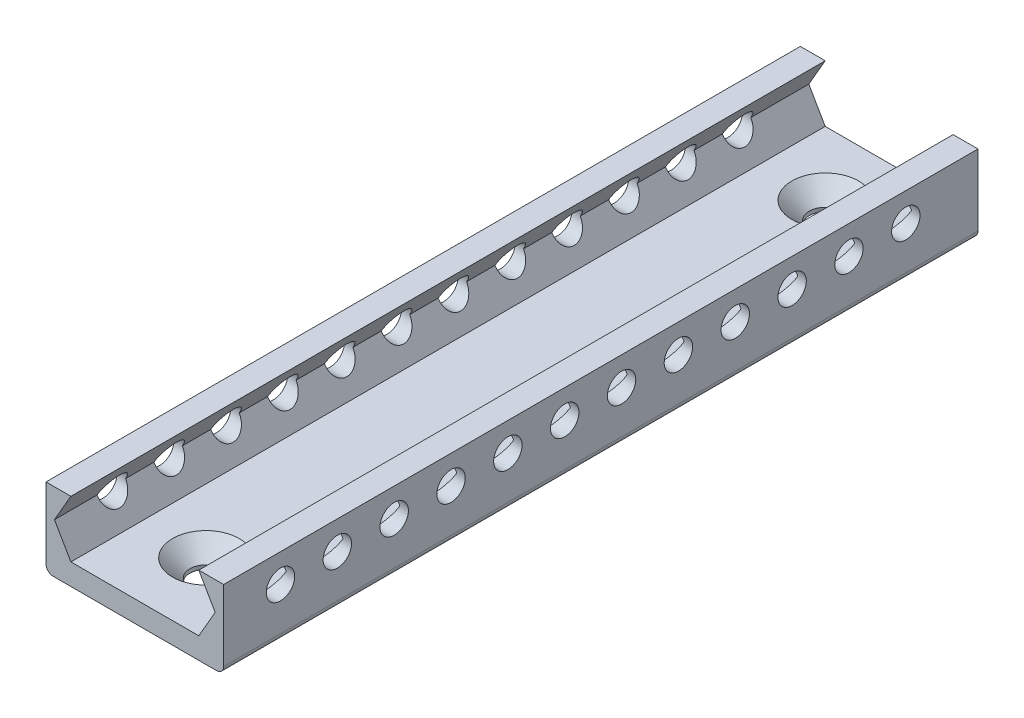
SolidWorks part; units mm, degrees
ref_plane "Front Plane" through (0, 0, 0) normal (0, 0, 1) x (1, 0, 0)
ref_plane "Top Plane" through (0, 0, 0) normal (0, 1, 0) x (1, 0, 0)
ref_plane "Right Plane" through (0, 0, 0) normal (1, 0, 0) x (0, 0, -1)
sketch "Sketch1" plane through (0, 0, 0) normal (0, 0, 1) x (1, 0, 0)
  line L0 (-9, 0) -> (9, 0)
  line L1 (-9, 0) -> (-11.3094, 4)
  line L2 (-11.3094, 4) -> (-9, 8)
  line L3 (-9, 8) -> (9, 8) construction
  line L4 (9, 8) -> (11.3094, 4)
  line L5 (11.3094, 4) -> (9, 0)
  line L6 (-9, 0) -> (-12.5, 0) construction
  line L8 (-12.5, 8) -> (-9, 8)
  line L9 (9, 8) -> (12.5, 8)
  line L10 (12.5, 8) -> (12.5, -3)
  line L11 (-12.5, 8) -> (-12.5, -3)
  line L12 (-12.5, -3) -> (12.5, -3)
  dimension "D1" = 18
  dimension "D2" = 120
  dimension "D3" = 120
  dimension "D4" = 120
  dimension "D5" = 120
  dimension "D6" = 8
  dimension "D7" = 3
  dimension "D8" = 3.5
extrude "Boss-Extrude1" add sketch "Sketch1" against normal blind 106.1617
sketch "Sketch2" plane through (0, 0, 0) normal (0, 1, 0) x (1, 0, 0)
  line L0 (9, 106.1617) -> (-9, 106.1617) construction
  line L1 (9, 0) -> (-9, 0) construction
  line L2 (0, 124.6082) -> (0, -49875.3918) construction
  circle A0 centre (0, 97.1617) radius 2
  circle A1 centre (0, 10) radius 2
  point P14 (0, 106.1617)
  dimension "D1" = 4
  dimension "D2" = 9
  dimension "D3" = 10
sketch "Sketch3" plane through (12.5, 0, 0) normal (1, 0, 0) x (0, 0, -1)
  line L0 (106.1617, 4) -> (0, 4) construction
  line L1 (0, -3) -> (0, 8) construction
  circle A0 centre (8, 4) radius 2
  dimension "D1" = 4
  dimension "D2" = 8
extrude "Cut-Extrude2" cut sketch "Sketch3" against normal blind 100
pattern_linear "LPattern1" count 12 spacing 8 along (0, 0, -1) of "Cut-Extrude2"
fillet "Fillet1" radius 1 2 edges at (12.5, -3, -53.0808) (-12.5, -3, -53.0808)
hole_wizard "CSK for M4 Flat Head Machine Screw1" positions "Sketch6" profile "Sketch7" countersink size "M4" standard "ANSI Metric" end condition through all
sketch "Sketch6" plane through (0, 0, 0) normal (0, 1, 0) x (1, 0, 0)
  point P0 (0, 97.1617)
  point P3 (0, 10)
sketch "Sketch7" plane through (0, 0, -97.1617) normal (1, 0, 0) x (0, 0, 1)
  line L0 (0, 0) -> (0, 3)
  line L1 (0, 3) -> (2.25, 3)
  line L2 (2.25, 3) -> (2.25, 2.45)
  line L3 (2.25, 2.45) -> (4.7, 0)
  line L5 (4.7, 0) -> (0, 0)
  line L6 (-2.25, 2.45) -> (-4.7, 0) construction
  line L11 (0, -6.35) -> (0, 107.95) construction
  dimension "Thru Hole Dia." = 4.5
  dimension "Thru Hole Depth" = 3
  dimension "Near C'Sink Dia." = 9.4
  dimension "Near C'Sink Angle" = 90
